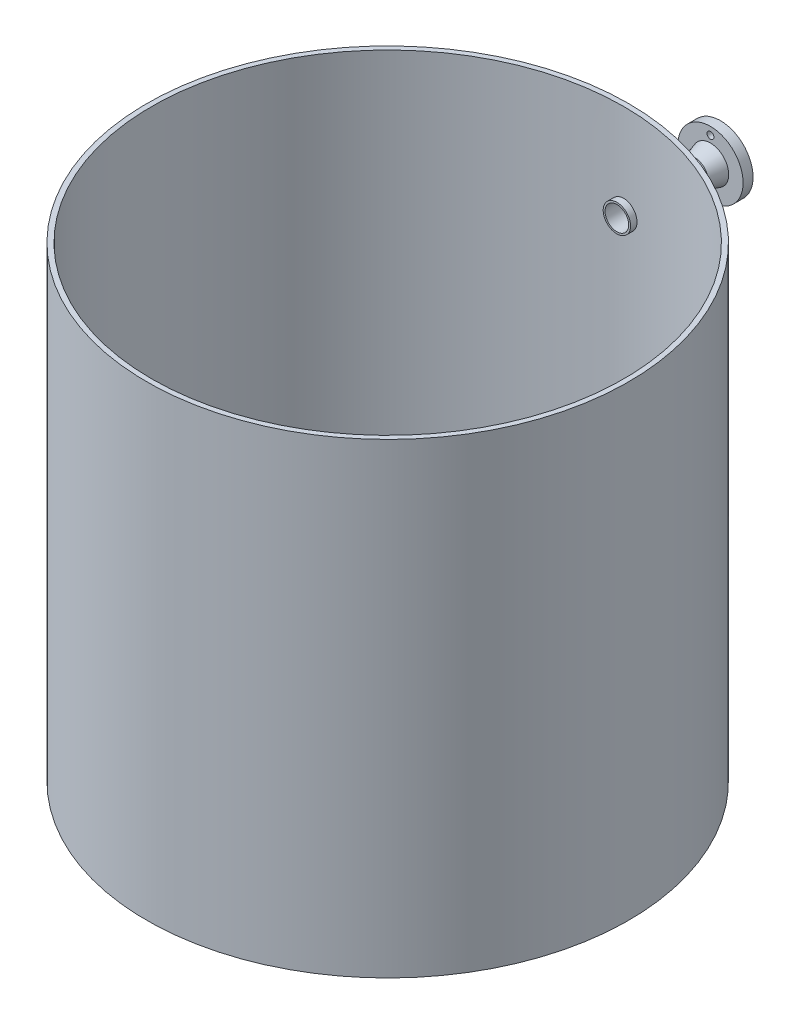
SolidWorks part; units mm, degrees
ref_plane "Front Plane" through (0, 0, 0) normal (0, 0, 1) x (1, 0, 0)
ref_plane "Top Plane" through (0, 0, 0) normal (0, 1, 0) x (1, 0, 0)
ref_plane "Right Plane" through (0, 0, 0) normal (1, 0, 0) x (0, 0, -1)
sketch "Sketch1" plane through (0, 0, 0) normal (0, 0, 1) x (1, 0, 0)
  line L0 (0, 0) -> (0, 1500) construction
  line L1 (0, 0) -> (775, 0) construction
  line L2 (775, 0) -> (775, 1500)
  line L3 (775, 1500) -> (759, 1500)
  line L4 (759, 1500) -> (759, 0)
  line L5 (759, 0) -> (775, 0)
  dimension "D1" = 1500
  dimension "D2" = 775
  dimension "D3" = 16
  dimension "D4" = 1500
revolve "Revolve1" add sketch "Sketch1" angle 360 about L0
sketch "Sketch2" plane through (0, 0, 0) normal (1, 0, 0) x (0, 0, -1)
  line L0 (775, 1500) -> (775, 1200) construction
  line L1 (775, 0) -> (775, 1500) construction
  line L2 (775, 1200) -> (1070, 1200) construction
  line L3 (1070, 1200) -> (1070, 1305) construction
  line L4 (1070, 1200) -> (1070, 1238) construction
  line L5 (1070, 1238) -> (737, 1238)
  line L6 (737, 1238) -> (737, 1244)
  line L7 (737, 1244) -> (987, 1244)
  line L8 (987, 1244) -> (1038, 1258.624)
  line L9 (1038, 1258.624) -> (1038, 1305) construction
  line L10 (1038, 1305) -> (1070, 1305)
  line L11 (1070, 1200) -> (1070, 1280) construction
  line L12 (1070, 1269) -> (1070, 1291) construction
  line L19 (1038, 1258.624) -> (1038, 1305)
  line L20 (1070, 1238) -> (1070, 1305)
  point P5 (0, 0)
  point P17 (1070, 1280)
  point P18 (0, 0)
  dimension "D1" = 300
  dimension "D2" = 295
  dimension "D3" = 105
  dimension "D4" = 38
  dimension "D5" = 333
  dimension "D6" = 6
  dimension "D7" = 250
  dimension "D8" = 74
  dimension "D9" = 51
  dimension "D10" = 80
revolve "Revolve2" add sketch "Sketch2" angle 360 about L2
sketch "Sketch3" plane through (0, 0, -1070) normal (0, 0, -1) x (-1, 0, 0)
  line L0 (0, 1095) -> (0, 1305) construction
  line L1 (0, 1120) -> (0, 1280) construction
  circle A0 centre (0, 1200) radius 105 construction
  circle A1 centre (0, 1280) radius 11
  circle A2 centre (0, 1120) radius 11
  point P8 (0, 1200)
  dimension "D2" = 22
  dimension "D3" = 22
  dimension "D1" = 160
extrude "Cut-Extrude1" cut sketch "Sketch3" against normal up to surface (32 mm away) up to face at (58.624, 1200, -1038)
sketch "Sketch4" plane through (0, 0, -1070) normal (0, 0, -1) x (-1, 0, 0)
  circle A0 centre (0, 1200) radius 38
extrude "Cut-Extrude2" cut sketch "Sketch4" against normal blind 400
